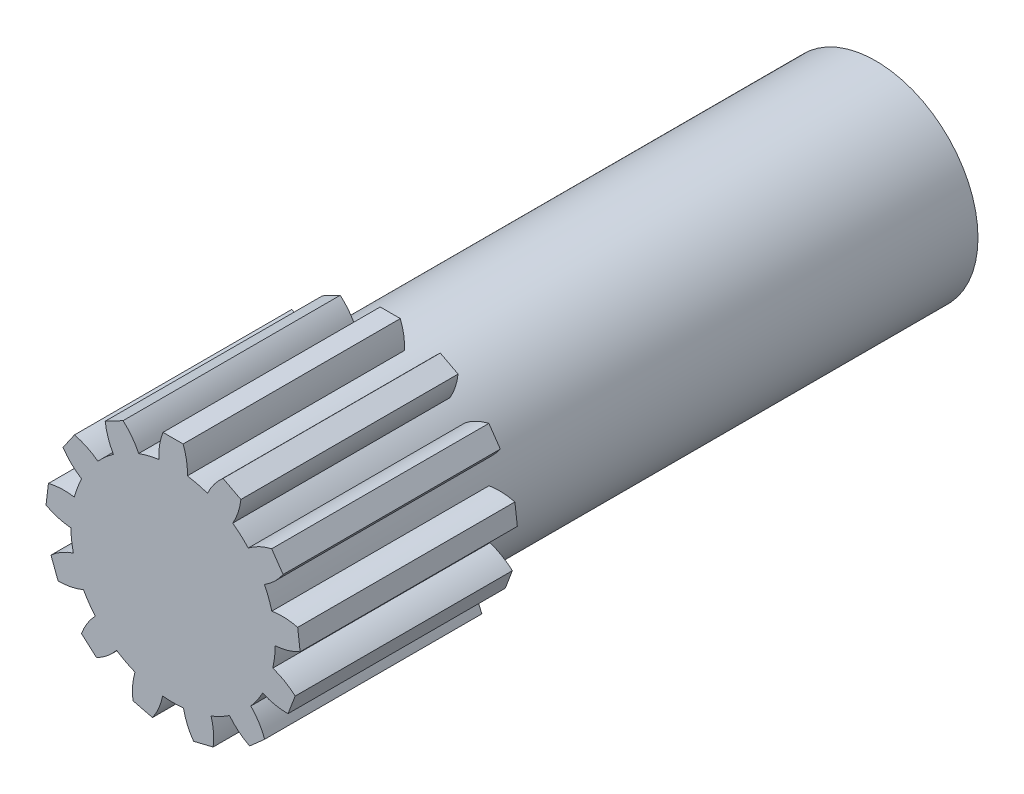
SolidWorks part; units mm, degrees
material "AISI 1020"
ref_plane "Front Plane" through (0, 0, 0) normal (0, 0, 1) x (1, 0, 0)
ref_plane "Top Plane" through (0, 0, 0) normal (0, 1, 0) x (1, 0, 0)
ref_plane "Right Plane" through (0, 0, 0) normal (1, 0, 0) x (0, 0, -1)
sketch "Sketch1" plane through (0, 0, 0) normal (0, 0, 1) x (1, 0, 0)
  circle A0 centre (0, 0) radius 8
extrude "Boss-Extrude1" add sketch "Sketch1" along normal blind 55
sketch "Sketch2" plane through (0, 0, 55) normal (0, 0, 1) x (1, 0, 0)
  line L2 (0, 8) -> (0, 9.9216) construction
  line L3 (-0.7871, 9.9216) -> (0.7871, 9.9216)
  arc A0 (1.1152, 7.9219) -> (-1.1152, 7.9219) centre (0, 0) ccw
  arc A1 (-1.1152, 7.9219) -> (-0.7871, 9.9216) centre (3.7558, 8.1496) cw
  arc A2 (1.1152, 7.9219) -> (0.7871, 9.9216) centre (-3.7558, 8.1496) ccw
  point P8 (0, 7.9219)
  point P12 (0, 9.9216)
extrude "Boss-Extrude2" add sketch "Sketch2" against normal blind 17
pattern_circular "CirPattern1" count 13 over 360 about axis through (0, 0, 0) along (0, 0, 1) of "Boss-Extrude2"
